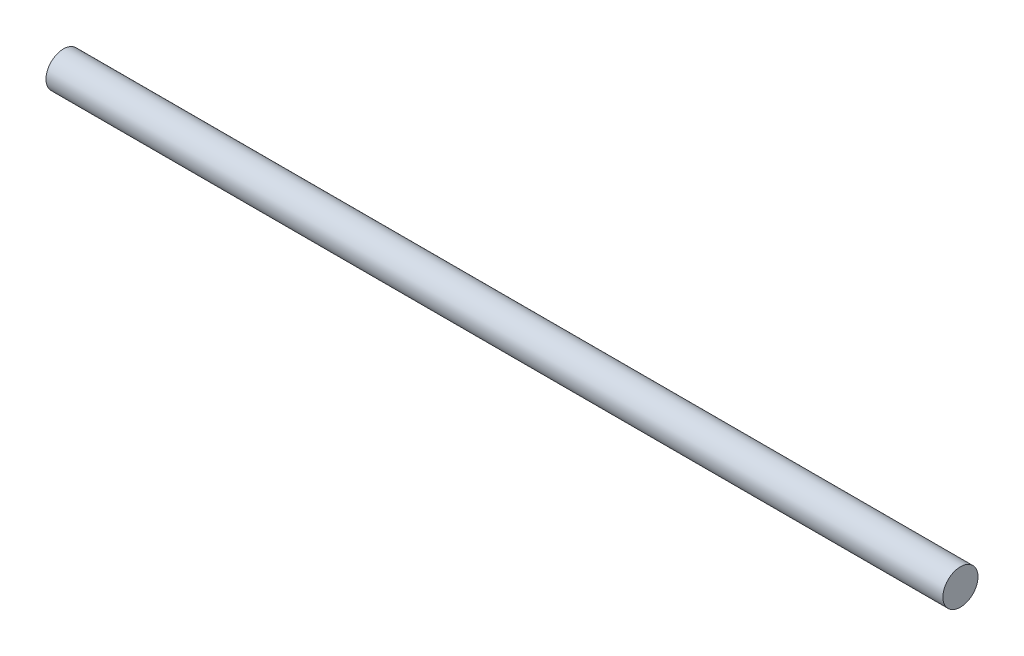
SolidWorks part; units mm, degrees
material "Zoltek Panex 33"
ref_plane "Front Plane" through (0, 0, 0) normal (0, 0, 1) x (1, 0, 0)
ref_plane "Top Plane" through (0, 0, 0) normal (0, 1, 0) x (1, 0, 0)
ref_plane "Right Plane" through (0, 0, 0) normal (1, 0, 0) x (0, 0, -1)
sketch "Sketch1" plane through (0, 0, 0) normal (1, 0, 0) x (0, 0, -1)
  circle A0 centre (0, 0) radius 9
  dimension "D1" = 18
extrude "Boss-Extrude1" add sketch "Sketch1" along normal mid plane 460
